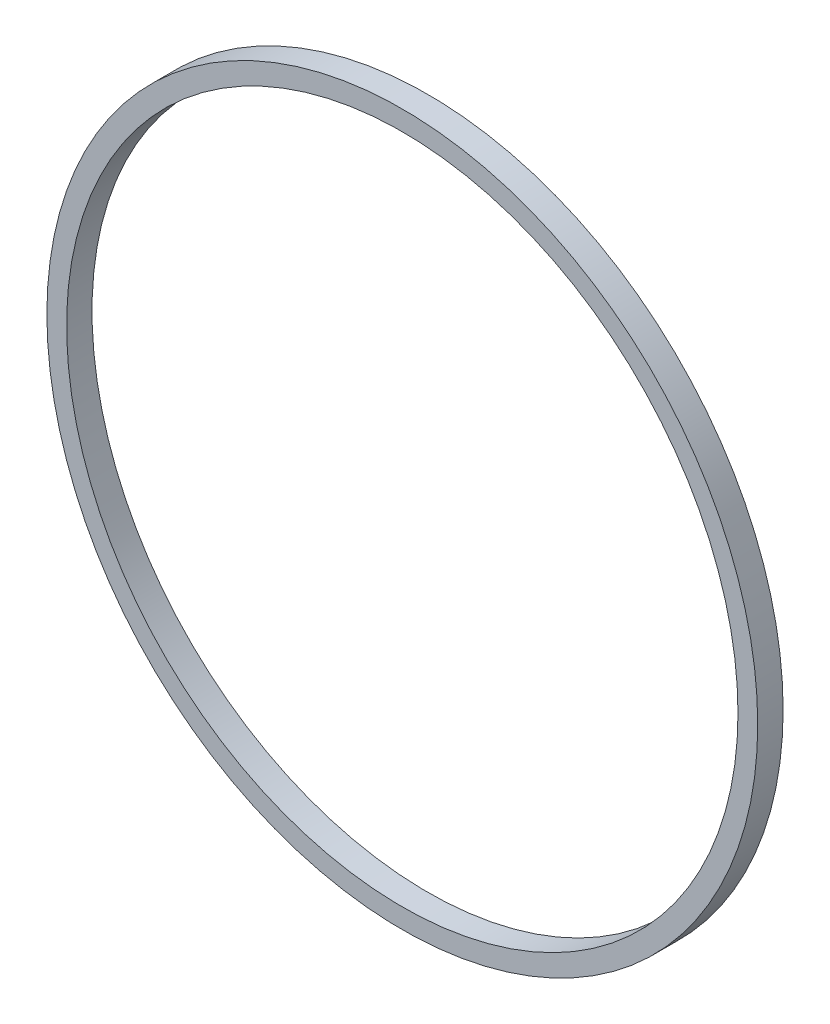
SolidWorks part; units mm, degrees
ref_plane "Front Plane" through (0, 0, 0) normal (0, 0, 1) x (1, 0, 0)
ref_plane "Top Plane" through (0, 0, 0) normal (0, 1, 0) x (1, 0, 0)
ref_plane "Right Plane" through (0, 0, 0) normal (1, 0, 0) x (0, 0, -1)
sketch "Sketch1" plane through (0, 0, 0) normal (0, 0, 1) x (1, 0, 0)
  arc B0 (9.4233, 171.953) -> (5.1903, 15.2885) centre (166.2366, 89.3266) ccw
  arc B1 (13.0798, 10.4448) -> (150.8717, 85.1111) centre (6.2297, 187.5624) ccw
  arc B2 (151.1218, 94.3656) -> (17.5629, 176.3637) centre (1.1585, -0.1256) ccw
  circle B3 centre (57.875, 92.2544) radius 58.5
  circle B4 centre (57.875, 92.2544) radius 55
  circle B5 centre (57.875, 92.2544) radius 59.5
  circle B6 centre (57.875, 92.2544) radius 63
sketch_block_instance "Block1-1"
sketch_block "Block1"
extrude "Boss-Extrude1" add sketch "Sketch1" along normal mid plane 4.5 contours B6 B5
